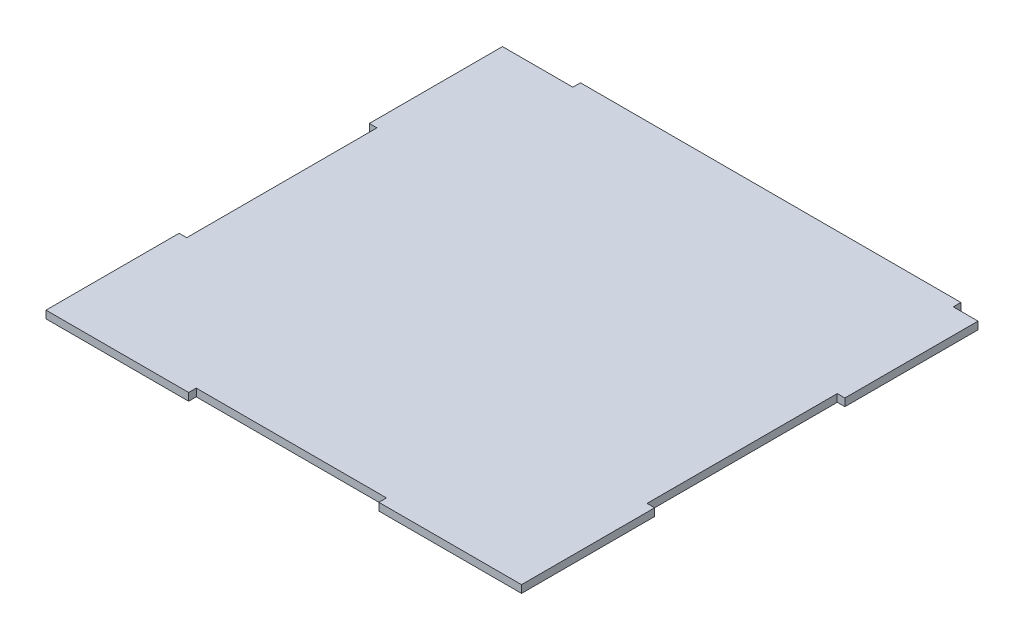
SolidWorks part; units mm, degrees
ref_plane "Front Plane" through (0, 0, 0) normal (0, 0, 1) x (1, 0, 0)
ref_plane "Top Plane" through (0, 0, 0) normal (0, 1, 0) x (1, 0, 0)
ref_plane "Right Plane" through (0, 0, 0) normal (1, 0, 0) x (0, 0, -1)
sketch "Sketch1" plane through (0, 0, 0) normal (0, 1, 0) x (1, 0, 0)
  line L0 (37, 240) -> (37, 244)
  line L1 (0, 0) -> (75, 0)
  line L2 (0, 0) -> (0, 70)
  line L3 (0, 240) -> (37, 240)
  line L4 (250, 0) -> (250, 70)
  line L5 (37, 244) -> (237, 244)
  line L6 (237, 244) -> (237, 240)
  line L7 (237, 240) -> (250, 240)
  line L8 (175, 0) -> (250, 0)
  line L10 (75, 0) -> (75, 4)
  line L11 (75, 4) -> (175, 4)
  line L12 (175, 0) -> (175, 4)
  line L13 (0, 170) -> (0, 240)
  line L14 (0, 170) -> (4, 170)
  line L16 (0, 70) -> (4, 70)
  line L17 (4, 170) -> (4, 70)
  line L18 (250, 170) -> (246, 170)
  line L20 (250, 70) -> (246, 70)
  line L21 (246, 170) -> (246, 70)
  line L22 (250, 170) -> (250, 240)
  dimension "D1" = 240
  dimension "D2" = 250
  dimension "D3" = 4
  dimension "D4" = 100
  dimension "D5" = 75
  dimension "D6" = 100
  dimension "D7" = 100
  dimension "D8" = 4
  dimension "D9" = 4
  dimension "D10" = 70
  dimension "D11" = 70
extrude "Boss-Extrude1" add sketch "Sketch1" along normal blind 4 contours L2 L16 L17 L14 L13 L3 L0 L5 L6 L7 L22 L18 L21 L20 L4 L8 L12 L11 L10 L1
